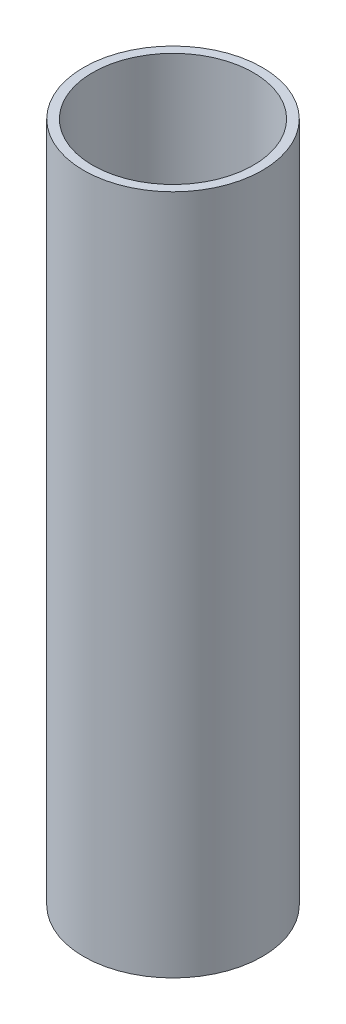
SolidWorks part; units mm, degrees
material "Teak"
ref_plane "Front Plane" through (0, 0, 0) normal (0, 0, 1) x (1, 0, 0)
ref_plane "Top Plane" through (0, 0, 0) normal (0, 1, 0) x (1, 0, 0)
ref_plane "Right Plane" through (0, 0, 0) normal (1, 0, 0) x (0, 0, -1)
sketch "Sketch1" plane through (0, 0, 0) normal (0, 1, 0) x (1, 0, 0)
  circle A0 centre (0, 0) radius 20
  circle A1 centre (0, 0) radius 18
  dimension "D1" = 2
  dimension "D2" = 40
extrude "Boss-Extrude1" add sketch "Sketch1" along normal blind 152.5
